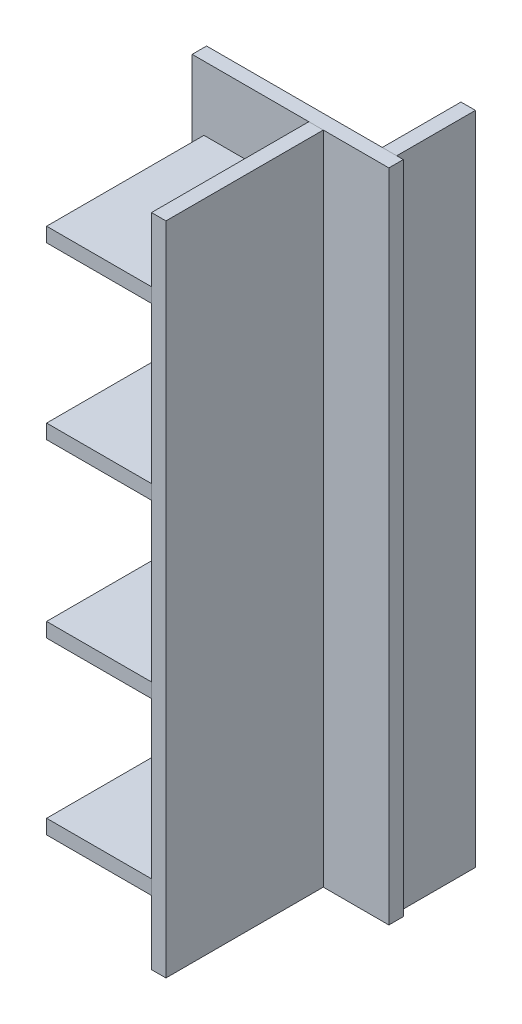
SolidWorks part; units mm, degrees
material "Kiefer"
ref_plane "Ebene vorne" through (0, 0, 0) normal (0, 0, 1) x (1, 0, 0)
ref_plane "Ebene oben" through (0, 0, 0) normal (0, 1, 0) x (1, 0, 0)
ref_plane "Ebene rechts" through (0, 0, 0) normal (1, 0, 0) x (0, 0, -1)
sketch "Skizze1" plane through (0, 0, 0) normal (0, 0, 1) x (1, 0, 0)
  line L0 (0, 540.7524) -> (0, -735.1097) construction
  line L1 (0, 0) -> (420.6573, 0) construction
  line L2 (-150, 500) -> (150, 500)
  line L3 (-150, 500) -> (-150, -500)
  line L4 (-150, -500) -> (150, -500)
  line L5 (150, 500) -> (150, -500)
  dimension "D1" = 1000
  dimension "D2" = 300
extrude "Aufsatz-Linear austragen1" add sketch "Skizze1" along normal blind 22
sketch "Skizze2" plane through (0, 0, 22) normal (0, 0, 1) x (1, 0, 0)
  line L0 (150, 500) -> (-150, 500) construction
  line L1 (28, 500) -> (50, 500)
  line L2 (28, 500) -> (28, -500)
  line L3 (28, -500) -> (50, -500)
  line L4 (50, 500) -> (50, -500)
  line L5 (-150, -500) -> (150, -500) construction
  line L6 (150, -500) -> (150, 500) construction
  dimension "D1" = 100
  dimension "D2" = 22
extrude "Aufsatz-Linear austragen2" add sketch "Skizze2" along normal blind 240 separate body
sketch "Skizze3" plane through (0, 0, 22) normal (0, 0, 1) x (1, 0, 0)
  line L0 (0, 0) -> (253.93, 0) construction
  line L1 (28, 500) -> (28, -500) construction
  line L2 (28, -402) -> (-132, -402)
  line L3 (28, -402) -> (28, -380)
  line L4 (28, -380) -> (-132, -380)
  line L5 (-132, -402) -> (-132, -380)
  line L6 (28, 402) -> (28, 380)
  line L7 (28, -142) -> (-132, -142)
  line L8 (28, -142) -> (28, -120)
  line L9 (28, -120) -> (-132, -120)
  line L10 (-132, -142) -> (-132, -120)
  line L11 (28, 380) -> (-132, 380)
  line L12 (-132, 402) -> (-132, 380)
  line L13 (28, 402) -> (-132, 402)
  line L14 (28, 142) -> (28, 120)
  line L15 (28, 120) -> (-132, 120)
  line L16 (-132, 142) -> (-132, 120)
  line L17 (28, 142) -> (-132, 142)
  dimension "D1" = 22
  dimension "D2" = 160
  dimension "D3" = 380
  dimension "D4" = 120
  dimension "D5" = 240
  dimension "D6" = 238
extrude "Aufsatz-Linear austragen3" add sketch "Skizze3" along normal blind 240 separate body
sketch "Skizze4" plane through (0, 0, 0) normal (0, 0, -1) x (-1, 0, 0)
  line L0 (-150, 500) -> (150, 500) construction
  line L1 (-140, 500) -> (-118, 500)
  line L2 (-140, 500) -> (-140, -500)
  line L3 (-140, -500) -> (-118, -500)
  line L4 (-118, 500) -> (-118, -500)
  line L5 (150, -500) -> (-150, -500) construction
  line L6 (-150, -500) -> (-150, 500) construction
  dimension "D1" = 10
  dimension "D2" = 22
extrude "Aufsatz-Linear austragen4" add sketch "Skizze4" along normal blind 120 separate body
